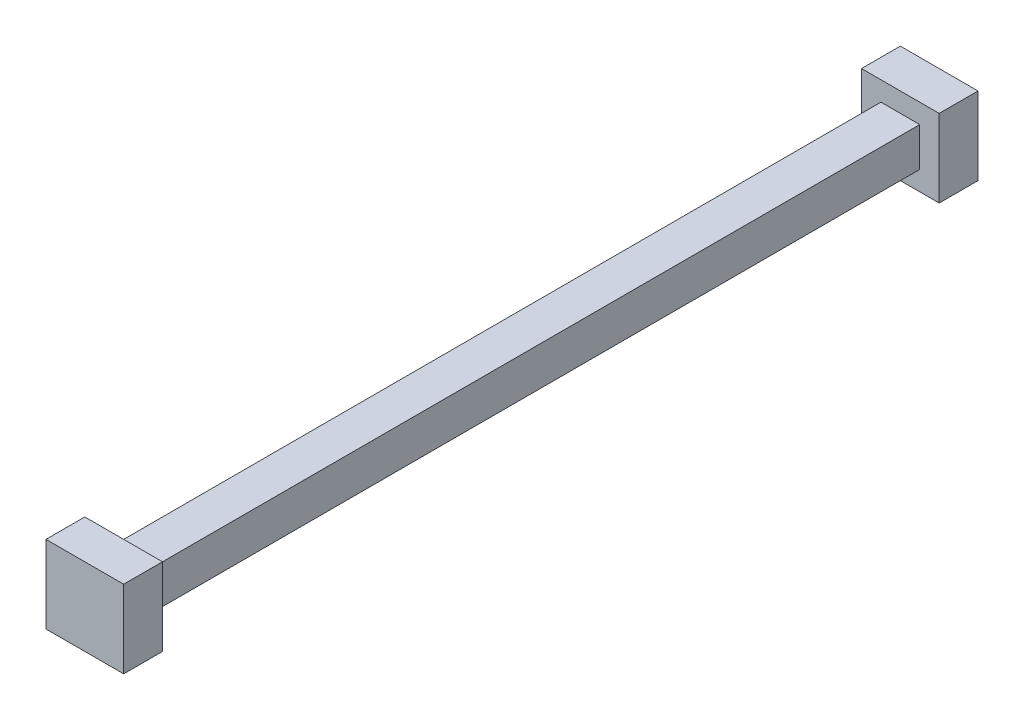
SolidWorks part; units mm, degrees
ref_plane "前视基准面" through (0, 0, 0) normal (0, 0, 1) x (1, 0, 0)
ref_plane "上视基准面" through (0, 0, 0) normal (0, 1, 0) x (1, 0, 0)
ref_plane "右视基准面" through (0, 0, 0) normal (1, 0, 0) x (0, 0, -1)
sketch "草图1" plane through (0, 0, 0) normal (0, 0, 1) x (1, 0, 0)
  line L1 (-5, -5) -> (5, -5)
  line L2 (-5, -5) -> (-5, 5)
  line L3 (-5, 5) -> (5, 5)
  line L4 (5, -5) -> (5, 5)
  line L5 (-5, -5) -> (5, 5) construction
  line L6 (-5, 5) -> (5, -5) construction
  point P0 (0, 0)
extrude "凸台-拉伸1" add sketch "草图1" along normal blind 200
sketch "草图2" plane through (0, 0, 200) normal (0, 0, 1) x (1, 0, 0)
  line L1 (-10, -10) -> (10, -10)
  line L2 (-10, -10) -> (-10, 10)
  line L3 (-10, 10) -> (10, 10)
  line L4 (10, -10) -> (10, 10)
  line L5 (-10, -10) -> (10, 10) construction
  line L6 (-10, 10) -> (10, -10) construction
  point P0 (0, 0)
extrude "凸台-拉伸2" add sketch "草图2" along normal blind 10
sketch "草图3" plane through (0, 0, 0) normal (0, 0, -1) x (-1, 0, 0)
  line L1 (-10, 10) -> (10, 10)
  line L2 (-10, 10) -> (-10, -10)
  line L3 (-10, -10) -> (10, -10)
  line L4 (10, 10) -> (10, -10)
  line L5 (-10, 10) -> (10, -10) construction
  line L6 (-10, -10) -> (10, 10) construction
  point P0 (0, 0)
extrude "凸台-拉伸3" add sketch "草图3" along normal blind 10
